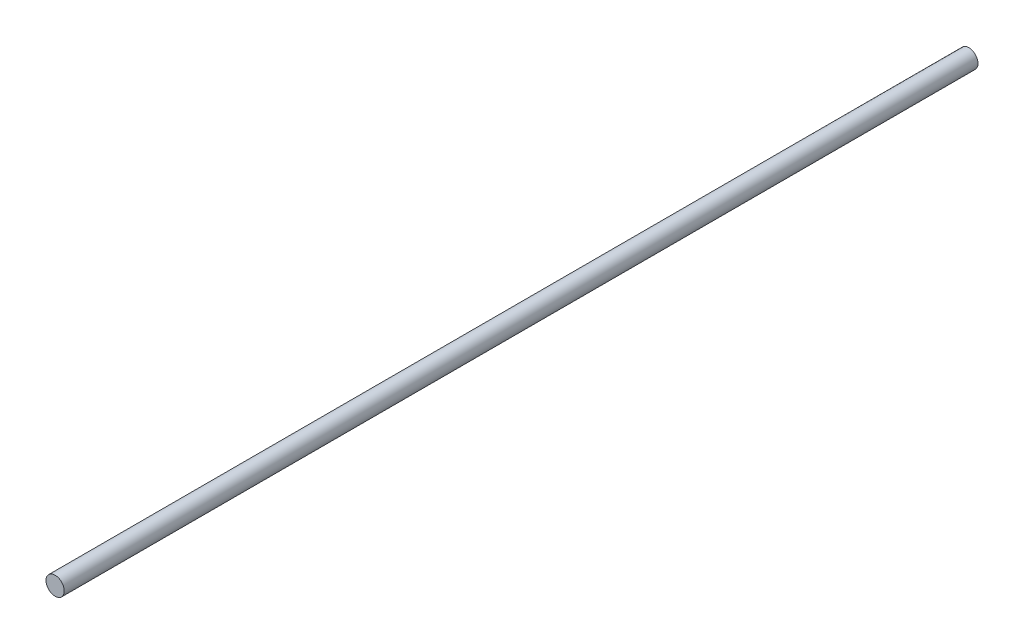
SolidWorks part; units mm, degrees
ref_plane "Plano frontal" through (0, 0, 0) normal (0, 0, 1) x (1, 0, 0)
ref_plane "Plano superior" through (0, 0, 0) normal (0, 1, 0) x (1, 0, 0)
ref_plane "Plano direito" through (0, 0, 0) normal (1, 0, 0) x (0, 0, -1)
sketch "Esboço1" plane through (0, 0, 0) normal (0, 0, 1) x (1, 0, 0)
  circle A0 centre (0, 0) radius 2.5
  dimension "D1" = 5
extrude "Ressalto-extrusão1" add sketch "Esboço1" along normal blind 250
